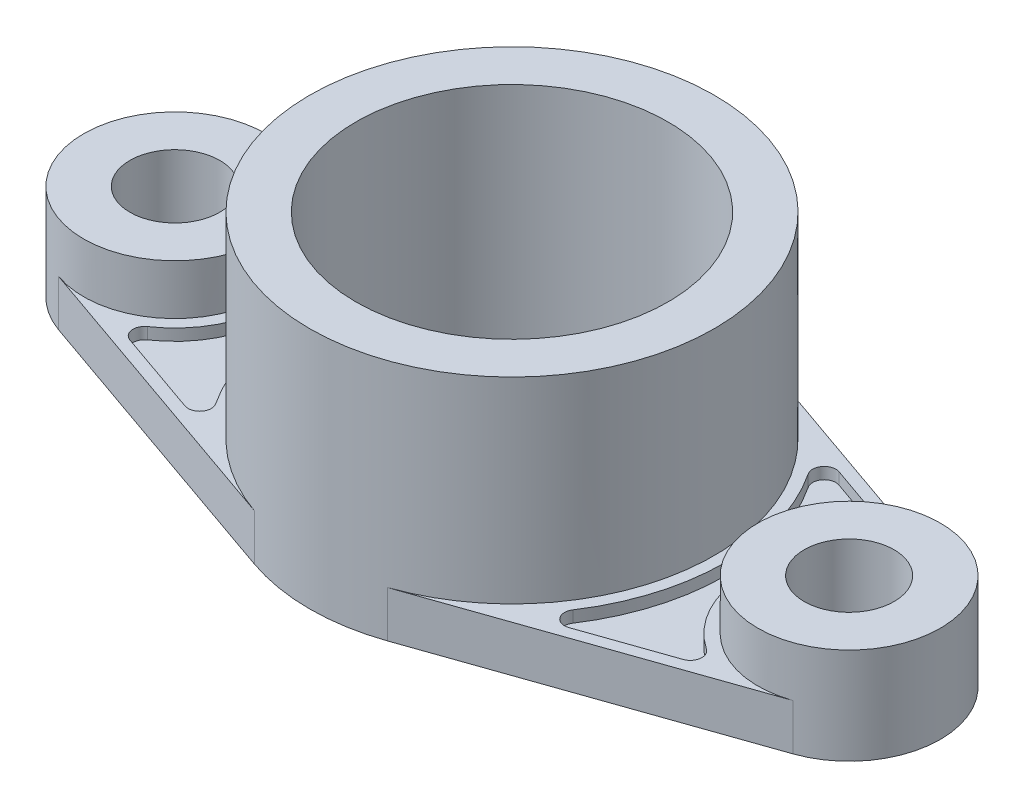
SolidWorks part; units mm, degrees
ref_plane "Płaszczyzna przednia" through (0, 0, 0) normal (0, 0, 1) x (1, 0, 0)
ref_plane "Płaszczyzna górna" through (0, 0, 0) normal (0, 1, 0) x (1, 0, 0)
ref_plane "Płaszczyzna prawa" through (0, 0, 0) normal (1, 0, 0) x (0, 0, -1)
sketch "Szkic1" plane through (0, 0, 0) normal (0, 1, 0) x (1, 0, 0)
  circle A0 centre (0, 0) radius 52.5
  circle A1 centre (0, 0) radius 40.5
  dimension "D2" = 105
  dimension "D1" = 12
extrude "Dodanie-wyciągnięcie3" add sketch "Szkic1" along normal blind 63
sketch "Szkic2" plane through (0, 0, 0) normal (0, 1, 0) x (1, 0, 0)
  line L0 (-110.9081, 0) -> (112.2103, 0) construction
  circle A0 centre (-87.5, 0) radius 11.665
  circle A1 centre (87.5, 0) radius 11.665
  circle A2 centre (-87.5, 0) radius 23.665
  circle A3 centre (87.5, 0) radius 23.665
  dimension "D1" = 23.33
  dimension "D2" = 23.33
  dimension "D3" = 87.5
  dimension "D4" = 175
  dimension "D5" = 12
extrude "Dodanie-wyciągnięcie4" add sketch "Szkic2" along normal blind 25 separate body
sketch "Szkic3" plane through (0, 0, 0) normal (0, 1, 0) x (1, 0, 0)
  line L0 (-17.301, 49.5674) -> (-95.2986, 22.3431)
  line L1 (-95.2986, -22.3431) -> (-17.301, -49.5674)
  line L2 (17.301, 49.5674) -> (95.2986, 22.3431)
  line L3 (17.301, -49.5674) -> (95.2986, -22.3431)
  circle A0 centre (0, 0) radius 52.5 construction
  circle A1 centre (-87.5, 0) radius 23.665 construction
  circle A2 centre (87.5, 0) radius 23.665 construction
  circle A3 centre (87.5, 0) radius 23.665 construction
  circle A4 centre (-87.5, 0) radius 23.665 construction
  circle A5 centre (0, 0) radius 52.5 construction
  circle A6 centre (87.5, 0) radius 23.665
  circle A7 centre (-87.5, 0) radius 23.665
  circle A8 centre (0, 0) radius 52.5
extrude "Dodanie-wyciągnięcie5" add sketch "Szkic3" along normal blind 12 contours A8 L0 A7 L1 | A8 L3 A6 L2
sketch "Szkic4" plane through (0, 12, 0) normal (0, 1, 0) x (1, 0, 0)
  line L1 (-49.826, 35.0373) -> (-71.8093, 27.3643)
  line L2 (-17.301, 49.5674) -> (-95.2986, 22.3431)
  line L3 (-95.2986, -22.3431) -> (-17.301, -49.5674)
  line L4 (-17.301, 49.5674) -> (-95.2986, 22.3431)
  line L5 (-95.2986, -22.3431) -> (-17.301, -49.5674)
  line L6 (-71.8093, -27.3643) -> (-49.826, -35.0373)
  line L7 (-78.3996, -25.064) -> (-40.0101, -38.4635) construction
  line L8 (-40.0101, 38.4635) -> (-78.3996, 25.064) construction
  line L9 (0, 0) -> (0, 22.051) construction
  line L10 (71.8093, -27.3643) -> (49.826, -35.0373)
  line L11 (49.826, 35.0373) -> (71.8093, 27.3643)
  arc A0 (-72.5075, -22.051) -> (-72.5075, 22.051) centre (-87.5, 0) ccw
  arc A1 (-46.3329, 30.5534) -> (-46.3329, -30.5534) centre (0, 0) ccw
  arc A2 (-17.301, 49.5674) -> (-17.301, -49.5674) centre (0, 0) ccw
  arc A3 (-95.2986, -22.3431) -> (-95.2986, 22.3431) centre (-87.5, 0) ccw
  arc A4 (-17.301, 49.5674) -> (-17.301, -49.5674) centre (0, 0) ccw
  arc A5 (-95.2986, -22.3431) -> (-95.2986, 22.3431) centre (-87.5, 0) ccw
  arc A6 (-78.3996, -25.064) -> (-78.3996, 25.064) centre (-87.5, 0) ccw construction
  arc A7 (-72.5075, -22.051) -> (-71.8093, -27.3643) centre (-70.8207, -24.5319) ccw
  arc A8 (-72.5075, 22.051) -> (-71.8093, 27.3643) centre (-70.8207, 24.5319) cw
  arc A9 (-40.0101, 38.4635) -> (-40.0101, -38.4635) centre (0, 0) ccw construction
  arc A10 (-46.3329, 30.5534) -> (-49.826, 35.0373) centre (-48.8374, 32.2049) ccw
  arc A11 (-49.826, -35.0373) -> (-46.3329, -30.5534) centre (-48.8374, -32.2049) ccw
  arc A12 (46.3329, 30.5534) -> (46.3329, -30.5534) centre (0, 0) cw
  arc A13 (49.826, -35.0373) -> (46.3329, -30.5534) centre (48.8374, -32.2049) cw
  arc A14 (72.5075, -22.051) -> (71.8093, -27.3643) centre (70.8207, -24.5319) cw
  arc A15 (72.5075, -22.051) -> (72.5075, 22.051) centre (87.5, 0) cw
  arc A16 (72.5075, 22.051) -> (71.8093, 27.3643) centre (70.8207, 24.5319) ccw
  arc A17 (46.3329, 30.5534) -> (49.826, 35.0373) centre (48.8374, 32.2049) cw
  dimension "D3" = 3
  dimension "D4" = 3
  dimension "D1" = 0
  dimension "D2" = 3
extrude "Wytnij-wyciągnięcie1" cut sketch "Szkic4" against normal blind 3 contours L1 A8 A0 A7 L6 A11 A1 A10 | A12 A13 L10 A14 A15 A16 L11 A17
